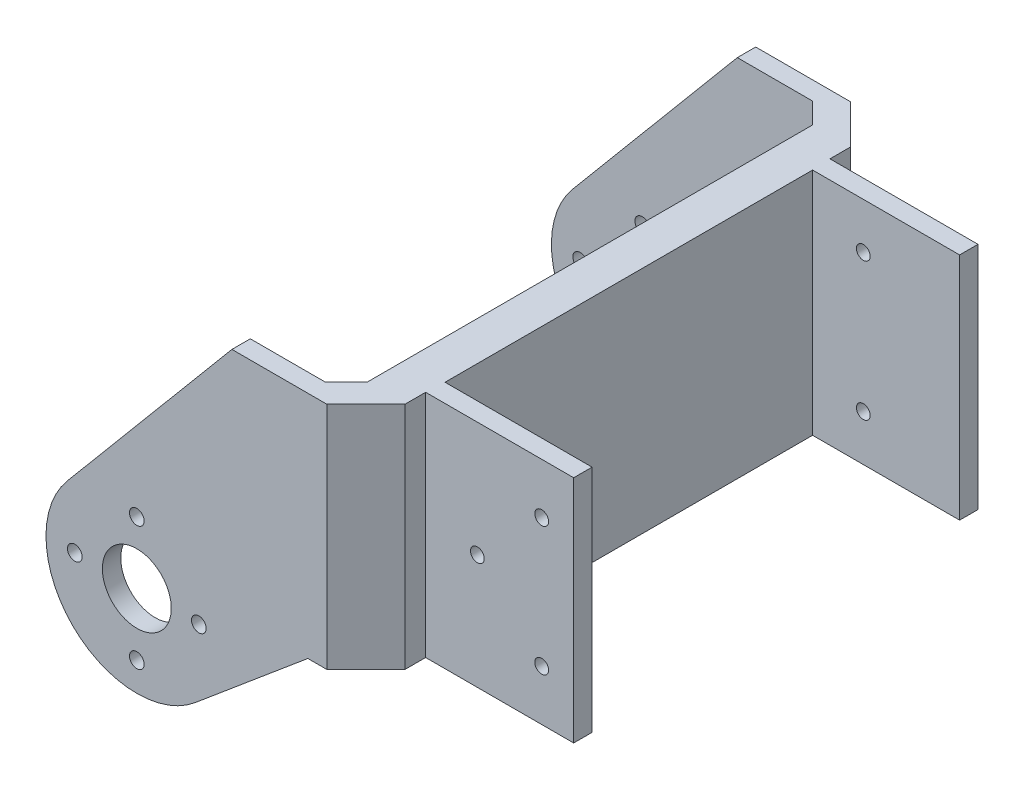
SolidWorks part; units mm, degrees
ref_plane "前视基准面" through (0, 0, 0) normal (0, 0, 1) x (1, 0, 0)
ref_plane "上视基准面" through (0, 0, 0) normal (0, 1, 0) x (1, 0, 0)
ref_plane "右视基准面" through (0, 0, 0) normal (1, 0, 0) x (0, 0, -1)
other "Configuration Table"
sketch "草图1" plane through (0, 0, 0) normal (0, 1, 0) x (1, 0, 0)
  line L0 (14.6774, 32.7097) -> (-1.3226, 32.7097)
  line L1 (-3.3226, 34.7097) -> (14.6774, 34.7097)
  line L2 (-3.3226, 34.7097) -> (-3.3226, -9.2903)
  line L3 (-3.3226, -9.2903) -> (14.6774, -9.2903)
  line L4 (14.6774, 34.7097) -> (14.6774, 32.7097)
  line L5 (-1.3226, 32.7097) -> (-1.3226, -7.2903)
  line L6 (-1.3226, -7.2903) -> (14.6774, -7.2903)
  line L7 (14.6774, -7.2903) -> (14.6774, -9.2903)
  dimension "D1" = 2
  dimension "D2" = 2
  dimension "D3" = 2
  dimension "D4" = 40
  dimension "D5" = 16
extrude "凸台-拉伸1" add sketch "草图1" along normal blind 25 contours L5 L6 L7 L3 L2 L1 L4 L0
sketch "草图2" plane through (0, 0, 9.2903) normal (0, 0, 1) x (1, 0, 0)
  line L1 (-3.3226, 25) -> (14.6774, 25) construction
  circle A0 centre (4.1958, 12.5) radius 0.75
  circle A1 centre (11.1958, 19.5) radius 0.75
  circle A2 centre (11.1958, 5.5) radius 0.75
  dimension "D1" = 14
  dimension "D2" = 5.5
  dimension "D3" = 7
  dimension "D4" = 7
extrude "切除-拉伸1" cut sketch "草图2" against normal up to next and the other way through all
ref_plane "基准面2" through (0, 0, -12.7097) normal (0, 0, 1) x (1, 0, 0)
sketch "草图5" plane through (0, 25, 0) normal (0, 1, 0) x (1, 0, 0)
  line L7 (-3.6828, 39.2097) -> (-1.4328, 36.9597)
  line L8 (-7.8226, 39.2097) -> (-16.0148, 39.2097)
  line L9 (-1.4328, 34.7097) -> (-3.3226, 34.7097)
  line L10 (-3.3226, 34.7097) -> (-3.3226, 32.4597)
  line L11 (-1.4328, 36.9597) -> (-1.4328, 34.7097)
  line L12 (-3.6828, 39.2097) -> (-5.6828, 41.2097)
  line L13 (-16.0148, 39.2097) -> (-16.0148, 41.2097)
  line L14 (-16.0148, 41.2097) -> (-5.6828, 41.2097)
  line L16 (-5.5726, 32.4597) -> (-5.5726, 36.9597)
  line L17 (-5.5726, 36.9597) -> (-7.8226, 39.2097)
  line L21 (-5.5726, 32.4597) -> (-5.5726, 12.7097)
  line L22 (-8.8, 12.7097) -> (8.8, 12.7097) construction
  line L23 (-5.5726, 12.7097) -> (-3.3226, 12.7097)
  line L24 (-3.3226, 34.7097) -> (-3.3226, -9.2903) construction
  line L25 (-3.3226, 12.7097) -> (-3.3226, 32.4597)
extrude "凸台-拉伸2" add sketch "草图5" against normal up to surface (25 mm away) up to face at (6.1774, 0, -12.7097)
mirror "镜向1" about plane through (0, 0, -12.7097) normal (0, 0, 1) of "凸台-拉伸2"
sketch "草图7" plane through (0, 0, -41.2097) normal (0, 0, -1) x (-1, 0, 0)
  line L0 (16.0148, 25) -> (33.9356, 3.6428)
  line L4 (16.0148, 0) -> (16.0148, 25)
  line L5 (7.7518, 0) -> (20.0084, -10.2845)
  line L6 (16.0148, 0) -> (5.6828, 0) construction
  line L7 (16.0148, 0) -> (7.7518, 0)
  arc A0 (20.0084, -10.2845) -> (33.9356, 3.6428) centre (26.3627, -2.7116) ccw
  dimension "D1" = 40
  dimension "D2" = 140
extrude "凸台-拉伸3" add sketch "草图7" against normal blind 2
mirror "镜向5" about plane through (0, 0, -12.7097) normal (0, 0, 1) of "凸台-拉伸3"
sketch "草图6" plane through (0, 0, -41.2097) normal (0, 0, -1) x (-1, 0, 0)
  circle A0 centre (26.3627, -2.7116) radius 3.75
  circle A1 centre (33.1127, -2.7116) radius 0.8
  circle A2 centre (26.3627, 4.0384) radius 0.8
  circle A3 centre (19.6127, -2.7116) radius 0.8
  circle A4 centre (26.3627, -9.4616) radius 0.8
  dimension "D1" = 6.75
  dimension "D2" = 6.75
  dimension "D3" = 6.75
  dimension "D4" = 6.75
extrude "切除-拉伸4" cut sketch "草图6" against normal through all both and the other way through all
sketch "草图8" plane through (0, 0, 9.2903) normal (0, 0, 1) x (1, 0, 0)
  circle A1 centre (4.1958, 20) radius 0.75
  circle A2 centre (4.1958, 5) radius 0.75
extrude "切除-拉伸5" cut sketch "草图8" against normal up to next from surface contours A1 | A2
